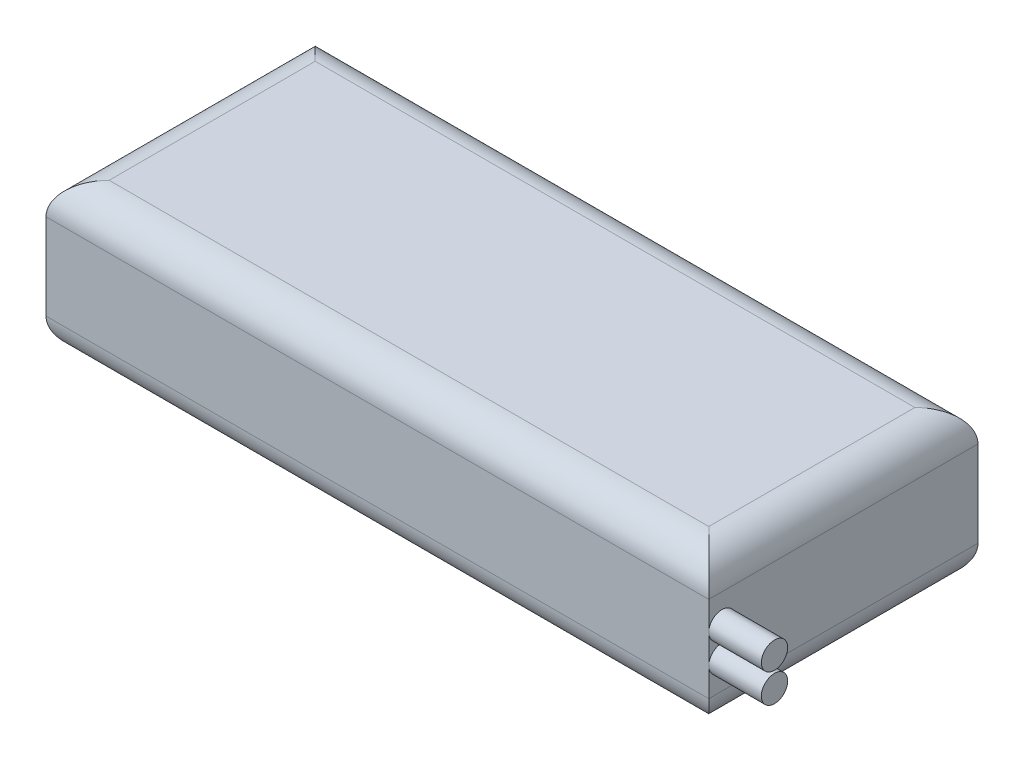
SolidWorks part; units mm, degrees
ref_plane "Front Plane" through (0, 0, 0) normal (0, 0, 1) x (1, 0, 0)
ref_plane "Top Plane" through (0, 0, 0) normal (0, 1, 0) x (1, 0, 0)
ref_plane "Right Plane" through (0, 0, 0) normal (1, 0, 0) x (0, 0, -1)
sketch "Sketch1" plane through (0, 0, 0) normal (0, 1, 0) x (1, 0, 0)
  line L1 (-41.084, 17.2443) -> (118.916, 17.2443)
  line L2 (-41.084, 17.2443) -> (-41.084, -47.7557)
  line L3 (-41.084, -47.7557) -> (118.916, -47.7557)
  line L4 (118.916, 17.2443) -> (118.916, -47.7557)
  dimension "D1" = 65
  dimension "D2" = 160
extrude "Boss-Extrude1" add sketch "Sketch1" along normal blind 36
sketch "Sketch2" plane through (118.916, 0, 0) normal (1, 0, 0) x (0, 0, -1)
  line L0 (-47.7557, 36) -> (-47.7557, 0) construction
  line L1 (-47.7557, 24.6675) -> (-41.4057, 24.6675) construction
  line L2 (-47.7557, 24.6675) -> (-47.7557, 11.3325) construction
  line L3 (-47.7557, 11.3325) -> (-41.4057, 11.3325) construction
  line L4 (-41.4057, 24.6675) -> (-41.4057, 11.3325) construction
  line L5 (17.2443, 18) -> (-89.592, 18) construction
  line L6 (17.2443, 36) -> (17.2443, 0) construction
  circle A0 centre (-44.5807, 21.4925) radius 3.175
  circle A1 centre (-44.5807, 14.5075) radius 3.175
  point P10 (-47.7557, 18)
  dimension "D1" = 13.335
  dimension "D2" = 6.35
extrude "Boss-Extrude3" add sketch "Sketch2" along normal blind 12.7
fillet "Fillet1" radius 7.62 8 edges at (38.916, 0, 47.7557) (118.916, 0, 15.2557) (38.916, 0, -17.2443) (-41.084, 0, 15.2557) (38.916, 36, -17.2443) (118.916, 36, 15.2557) (38.916, 36, 47.7557) (-41.084, 36, 15.2557)
